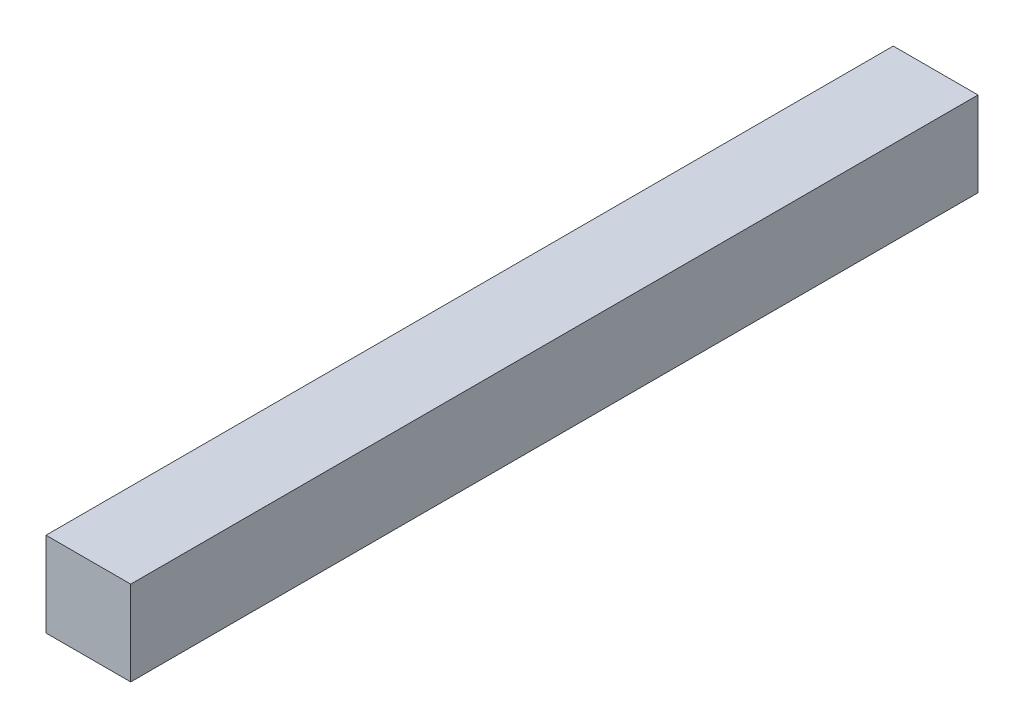
SolidWorks part; units mm, degrees
ref_plane "Front Plane" through (0, 0, 0) normal (0, 0, 1) x (1, 0, 0)
ref_plane "Top Plane" through (0, 0, 0) normal (0, 1, 0) x (1, 0, 0)
ref_plane "Right Plane" through (0, 0, 0) normal (1, 0, 0) x (0, 0, -1)
sketch "Sketch1" plane through (0, 0, 0) normal (0, 0, 1) x (1, 0, 0)
  line L1 (0, 0) -> (20, 0)
  line L2 (0, 0) -> (0, -20)
  line L3 (0, -20) -> (20, -20)
  line L4 (20, 0) -> (20, -20)
  dimension "D1" = 20
extrude "Boss-Extrude1" add sketch "Sketch1" along normal blind 200
